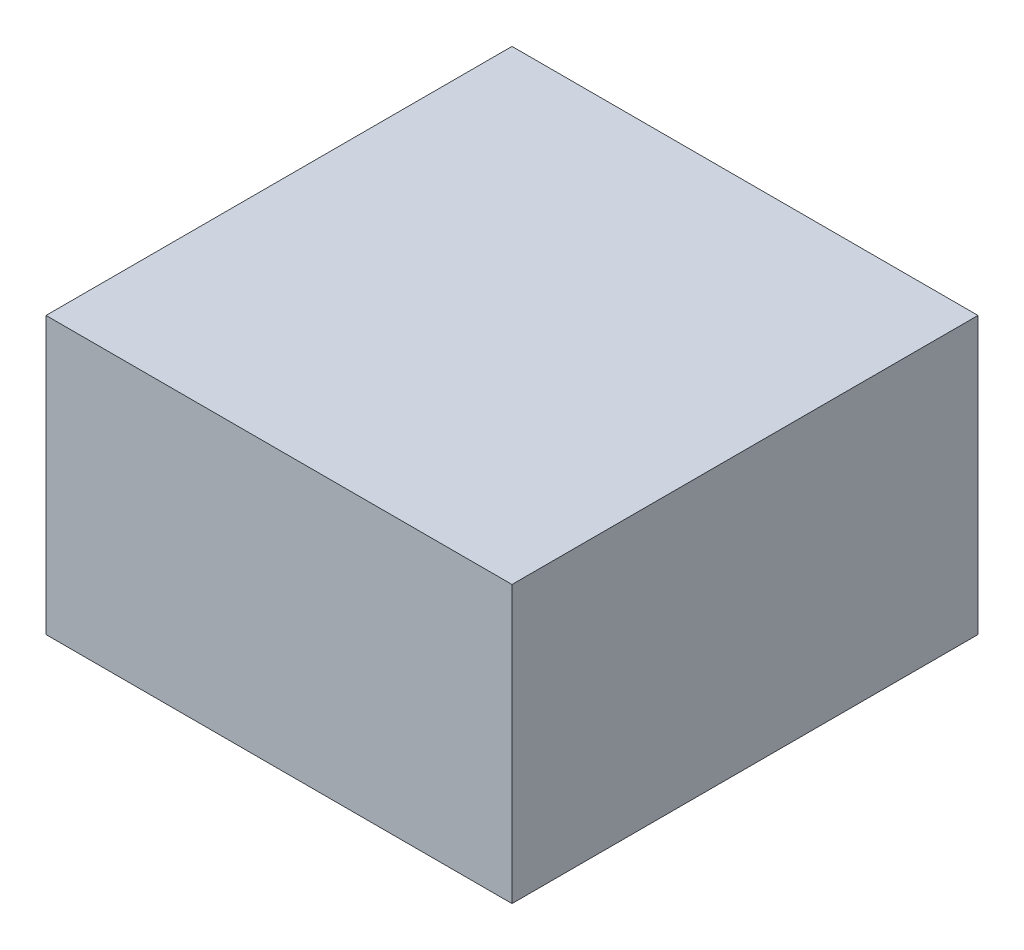
SolidWorks part; units mm, degrees
ref_plane "Спереди" through (0, 0, 0) normal (0, 0, 1) x (1, 0, 0)
ref_plane "Сверху" through (0, 0, 0) normal (0, 1, 0) x (1, 0, 0)
ref_plane "Справа" through (0, 0, 0) normal (1, 0, 0) x (0, 0, -1)
other "Configuration Table"
sketch "Эскиз1" plane through (0, 0, 0) normal (0, 1, 0) x (1, 0, 0)
  line L1 (21.75, -21.75) -> (-21.75, -21.75)
  line L2 (21.75, -21.75) -> (21.75, 21.75)
  line L3 (21.75, 21.75) -> (-21.75, 21.75)
  line L4 (-21.75, -21.75) -> (-21.75, 21.75)
  line L5 (21.75, -21.75) -> (-21.75, 21.75) construction
  line L6 (21.75, 21.75) -> (-21.75, -21.75) construction
  point P0 (0, 0)
extrude "Бобышка-Вытянуть1" add sketch "Эскиз1" along normal blind 25.8
sketch "Эскиз2" plane through (0, 0, 0) normal (0, -1, 0) x (1, 0, 0)
  circle A0 centre (-18.5, 18.5) radius 1.5
  circle A1 centre (18.5, 18.5) radius 1.5
  circle A2 centre (-18.5, -18.5) radius 1.5
  circle A3 centre (18.5, -18.5) radius 1.5
extrude "Вырез-Вытянуть1" cut sketch "Эскиз2" against normal blind 10
